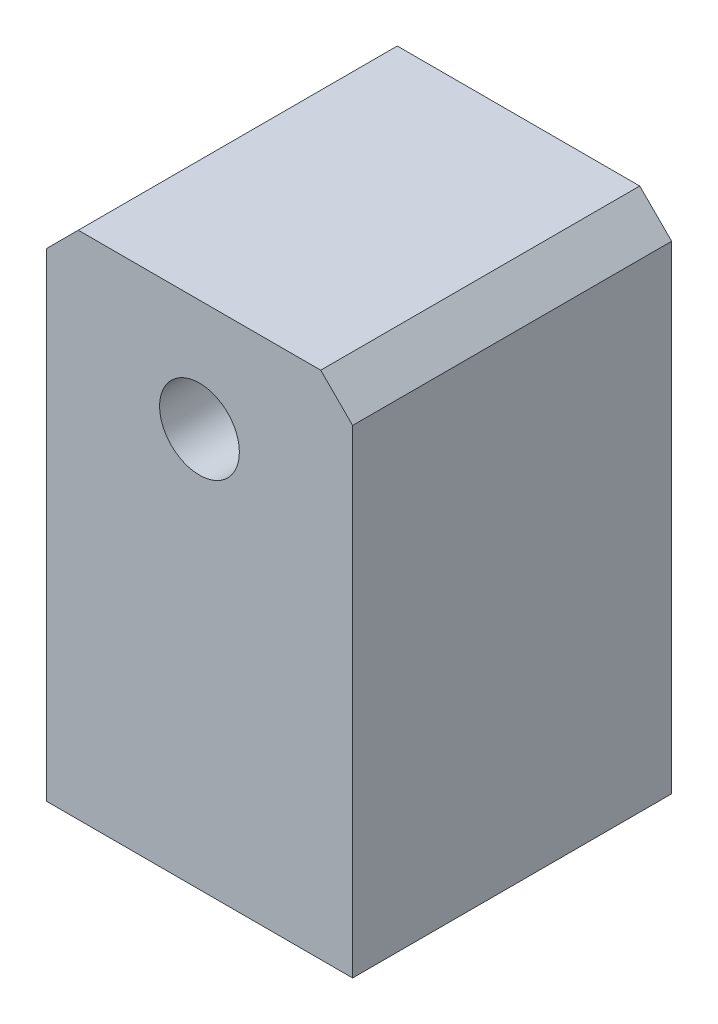
SolidWorks part; units mm, degrees
ref_plane "Plano frontal" through (0, 0, 0) normal (0, 0, 1) x (1, 0, 0)
ref_plane "Plano superior" through (0, 0, 0) normal (0, 1, 0) x (1, 0, 0)
ref_plane "Plano direito" through (0, 0, 0) normal (1, 0, 0) x (0, 0, -1)
sketch "Sketch1" plane through (0, 0, 0) normal (0, 0, 1) x (1, 0, 0)
  line L1 (-48, 0) -> (48, 0)
  line L2 (-48, 0) -> (-48, 160)
  line L3 (-48, 160) -> (48, 160)
  line L4 (48, 0) -> (48, 160)
  line L5 (0, 160) -> (0, 0) construction
  line L6 (-48, 80) -> (48, 80) construction
  point P272 (0, 80)
  dimension "D1" = 96
  dimension "D2" = 160
extrude "Boss-Extrude1" add sketch "Sketch1" along normal blind 100
sketch "Sketch2" plane through (0, 0, 100) normal (0, 0, 1) x (1, 0, 0)
  line L0 (0, 0) -> (0, 125) construction
  circle A0 centre (0, 125) radius 12.5
  dimension "D2" = 25
  dimension "D1" = 125
extrude "Cut-Extrude1" cut sketch "Sketch2" against normal through all
chamfer "Chamfer1" distance 10 angle 45 2 edges at (48, 160, 50) (-48, 160, 50)
